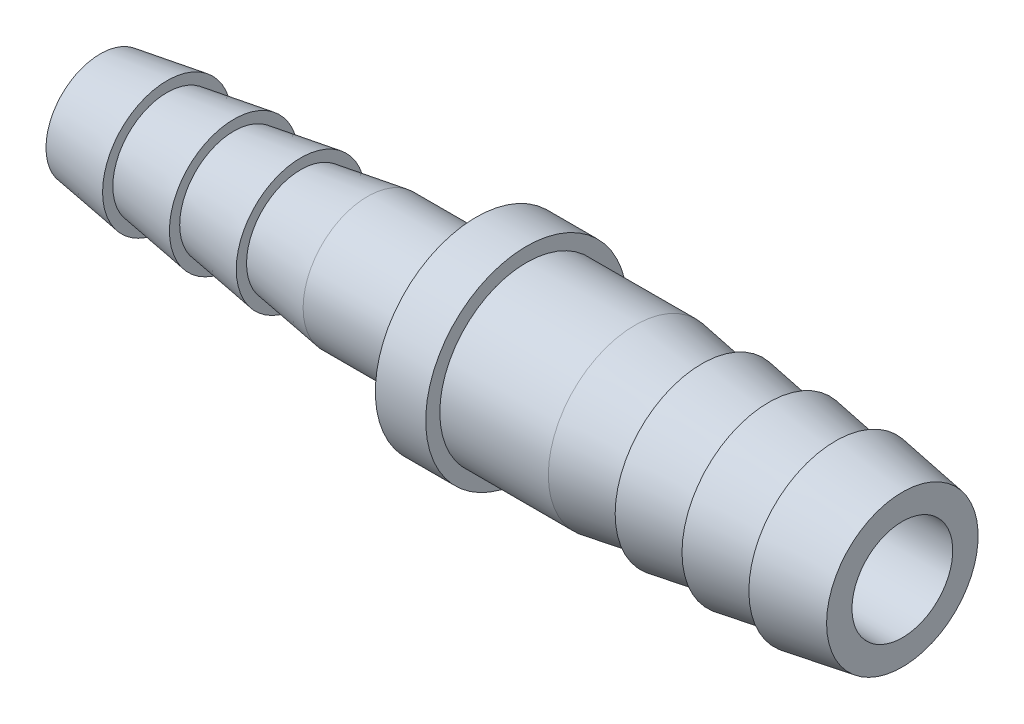
SolidWorks part; units mm, degrees
ref_plane "Front Plane" through (0, 0, 0) normal (0, 0, 1) x (1, 0, 0)
ref_plane "Top Plane" through (0, 0, 0) normal (0, 1, 0) x (1, 0, 0)
ref_plane "Right Plane" through (0, 0, 0) normal (1, 0, 0) x (0, 0, -1)
sketch "Sketch1" plane through (0, 0, 0) normal (0, 0, 1) x (1, 0, 0)
  line L0 (-25.273, 0) -> (25.273, 0) construction
  line L1 (-25.273, 4.064) -> (0, 4.064)
  line L2 (-25.273, 4.064) -> (-25.273, 1.905)
  line L3 (-25.273, 1.905) -> (0, 1.905)
  line L4 (0, 4.064) -> (0, 1.905)
  dimension "thru hole" = 3.81
  dimension "od" = 8.128
  dimension "overall" = 50.546
revolve "Revolve1" add sketch "Sketch1" angle 360 about L0
sketch "Sketch2" plane through (0, 0, 0) normal (0, 0, 1) x (1, 0, 0)
  line L0 (0, 0) -> (0, 1.905) construction
  line L1 (-1.5875, 6.35) -> (1.5875, 6.35)
  line L2 (-1.5875, 6.35) -> (-1.5875, 1.905)
  line L3 (-1.5875, 1.905) -> (1.5875, 1.905)
  line L4 (1.5875, 6.35) -> (1.5875, 1.905)
  line L5 (-25.273, 1.905) -> (0, 1.905) construction
  line L6 (0, 0) -> (-25.273, 0) construction
  dimension "D1" = 3.175
  dimension "center rib od" = 12.7
revolve "Revolve2" add sketch "Sketch2" angle 360 about L6
sketch "Sketch3" plane through (0, 0, 0) normal (0, 0, 1) x (1, 0, 0)
  line L0 (-25.273, 4.064) -> (-25.273, 3.4163)
  line L1 (-25.273, 3.4163) -> (-21.0608, 4.064)
  line L2 (-25.273, 4.064) -> (-21.0608, 4.064)
  dimension "D2" = 0.6477
  dimension "D1" = 4.2122
revolve "Cut-Revolve1" cut sketch "Sketch3" angle 360 about L0
pattern_linear "LPattern1" count 4 spacing 4.2122 along (1, 0, 0) of "Cut-Revolve1"
sketch "Sketch4" plane through (0, 0, 0) normal (0, 0, 1) x (1, 0, 0)
  line L0 (0, 0) -> (25.273, 0) construction
  line L1 (0, 5.461) -> (25.273, 5.461)
  line L2 (0, 5.461) -> (0, 3.175)
  line L3 (0, 3.175) -> (25.273, 3.175)
  line L4 (25.273, 5.461) -> (25.273, 3.175)
  dimension "large id" = 6.35
  dimension "large od" = 10.922
revolve "Revolve3" add sketch "Sketch4" angle 360 about L0
sketch "Sketch5" plane through (0, 0, 0) normal (0, 0, 1) x (1, 0, 0)
  line L0 (25.273, 5.461) -> (25.273, 4.7752)
  line L1 (25.273, 4.7752) -> (21.0608, 5.461)
  line L2 (25.273, 5.461) -> (21.0608, 5.461)
  dimension "D1" = 0.6858
  dimension "D2" = 4.2122
revolve "Cut-Revolve2" cut sketch "Sketch5" angle 360 about L0
pattern_linear "LPattern2" count 4 spacing 4.2122 along (-1, 0, 0) of "Cut-Revolve2"
sketch "Sketch6" plane through (0, 0, 0) normal (0, 0, 1) x (1, 0, 0)
  line L1 (0, 3.175) -> (2.032, 3.175)
  line L2 (0, 3.175) -> (0, 1.905)
  line L3 (0, 1.905) -> (2.032, 1.905)
  line L4 (2.032, 3.175) -> (2.032, 1.905)
  dimension "D1" = 2.032
revolve "Revolve4" add sketch "Sketch6" angle 360 about L0
equation "\"D1@Sketch3\" = \"overall@Sketch1\"/12"
equation "\"D3@LPattern1\" = \"D1@Sketch3\""
equation "\"D2@Sketch3\" = (\"od@Sketch1\"-\"thru hole@Sketch1\")*.15"
equation "\"D1@Sketch5\" = (\"large od@Sketch4\"-\"large id@Sketch4\")*.15"
equation "\"D2@Sketch5\" = \"overall@Sketch1\"/12"
equation "\"D3@LPattern2\" = \"D2@Sketch5\""
